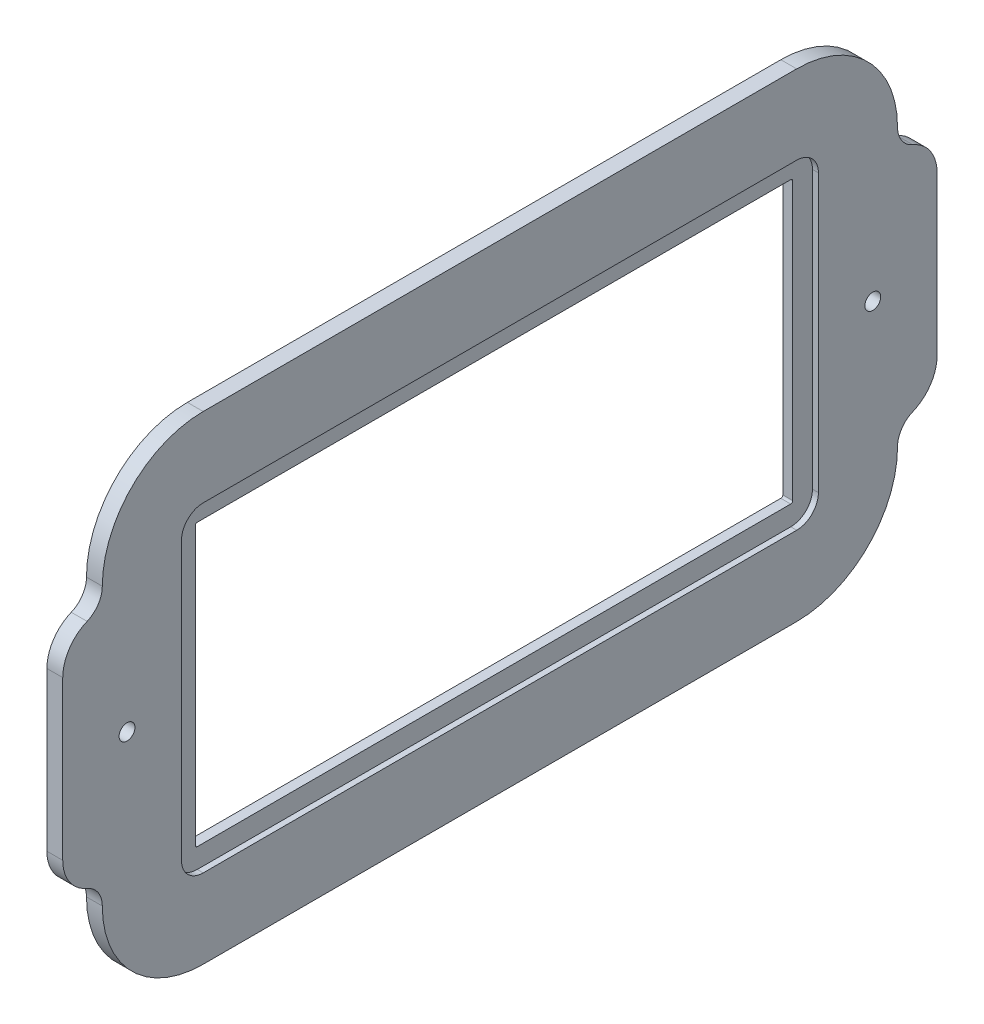
SolidWorks part; units mm, degrees
other "Weld Folder"
material "Ст 3 ГОСТ 380-88"
ref_plane "Front Plane" through (0, 0, 0) normal (0, 0, 1) x (1, 0, 0)
ref_plane "Top Plane" through (0, 0, 0) normal (0, 1, 0) x (1, 0, 0)
ref_plane "Right Plane" through (0, 0, 0) normal (1, 0, 0) x (0, 0, -1)
sketch "Sketch1" plane through (0, 0, 0) normal (0, 0, 1) x (1, 0, 0)
  line L0 (-3, 96) -> (-3, 81) construction
  line L1 (-3, 121) -> (-3, 81)
  line L2 (-3, 81) -> (-6, 81) construction
  line L3 (-3, 81) -> (-6, 81)
  line L4 (-6, 81) -> (-6, 71) construction
  line L5 (-6, 81) -> (-6, 71)
  line L6 (-3, 121) -> (-11, 121)
  line L7 (-11, 121) -> (-11, 71)
  line L8 (-11, 71) -> (-6, 71)
  dimension "D1" = 40
  dimension "D2" = 10
  dimension "D3" = 8
sketch "Sketch2" plane through (0, 0, 0) normal (1, 0, 0) x (0, 0, -1)
  line L4 (150, 92) -> (-150, 92)
  line L5 (-172, 70) -> (-172, -70)
  line L6 (-150, -92) -> (150, -92)
  line L7 (172, -70) -> (172, 70)
  line L8 (150, 92) -> (-150, 92)
  line L9 (-172, 70) -> (-172, -70)
  line L10 (-150, -92) -> (150, -92)
  line L11 (172, -70) -> (172, 70)
  arc A4 (-150, 92) -> (-172, 70) centre (-150, 70) ccw
  arc A5 (-172, -70) -> (-150, -92) centre (-150, -70) ccw
  arc A6 (150, -92) -> (172, -70) centre (150, -70) ccw
  arc A7 (172, 70) -> (150, 92) centre (150, 70) ccw
  arc A8 (-150, 92) -> (-172, 70) centre (-150, 70) ccw
  arc A9 (-172, -70) -> (-150, -92) centre (-150, -70) ccw
  arc A10 (150, -92) -> (172, -70) centre (150, -70) ccw
  arc A11 (172, 70) -> (150, 92) centre (150, 70) ccw
  dimension "D1" = 0
sweep "Sweep1" add profiles "Sketch1" path "Sketch2"
sketch "Sketch5" plane through (-11, 0, 0) normal (-1, 0, 0) x (0, 0, 1)
  line L0 (201, -70) -> (201, 70) construction
  line L1 (0, 121) -> (-150, 121) construction
  line L2 (-201, 70) -> (-201, -70) construction
  line L3 (-150, -121) -> (150, -121) construction
  line L4 (201, -70) -> (201, 70)
  line L5 (150, 121) -> (-150, 121)
  line L6 (-201, 70) -> (-201, -70)
  line L7 (-150, -121) -> (150, -121)
  line L8 (0, 71) -> (-150, 71) construction
  line L9 (-151, 70) -> (-151, -70) construction
  line L10 (150, 71) -> (0, 71) construction
  line L11 (-150, -71) -> (150, -71) construction
  line L12 (151, -70) -> (151, 70) construction
  line L13 (0, 71) -> (-150, 71)
  line L14 (-151, 70) -> (-151, -70)
  line L15 (150, 71) -> (0, 71)
  line L16 (-150, -71) -> (150, -71)
  line L17 (151, -70) -> (151, 70)
  arc A0 (201, 70) -> (150, 121) centre (150, 70) ccw construction
  arc A1 (-150, 121) -> (-201, 70) centre (-150, 70) ccw construction
  arc A2 (-201, -70) -> (-150, -121) centre (-150, -70) ccw construction
  arc A3 (150, -121) -> (201, -70) centre (150, -70) ccw construction
  arc A4 (201, 70) -> (150, 121) centre (150, 70) ccw
  arc A5 (-150, 121) -> (-201, 70) centre (-150, 70) ccw
  arc A6 (-201, -70) -> (-150, -121) centre (-150, -70) ccw
  arc A7 (150, -121) -> (201, -70) centre (150, -70) ccw
  arc A8 (-150, 71) -> (-151, 70) centre (-150, 70) ccw construction
  arc A9 (-151, -70) -> (-150, -71) centre (-150, -70) ccw construction
  arc A10 (151, 70) -> (150, 71) centre (150, 70) ccw construction
  arc A11 (150, -71) -> (151, -70) centre (150, -70) ccw construction
  arc A12 (-150, 71) -> (-151, 70) centre (-150, 70) ccw
  arc A13 (-151, -70) -> (-150, -71) centre (-150, -70) ccw
  arc A14 (151, 70) -> (150, 71) centre (150, 70) ccw
  arc A15 (150, -71) -> (151, -70) centre (150, -70) ccw
extrude "Boss-Extrude1" add sketch "Sketch5" against normal up to surface (8 mm away) up to face at (-3, 0, 181)
sketch "Sketch7" plane through (-3, 0, 0) normal (1, 0, 0) x (0, 0, -1)
  line L25 (161, -70) -> (161, 70)
  line L26 (-150, -81) -> (150, -81)
  line L27 (-161, 70) -> (-161, -70)
  line L28 (150, 81) -> (-150, 81)
  line L29 (161, -70) -> (161, 70)
  line L30 (-150, -81) -> (150, -81)
  line L31 (-161, 70) -> (-161, -70)
  line L32 (150, 81) -> (-150, 81)
  arc A19 (161, 70) -> (150, 81) centre (150, 70) ccw
  arc A20 (150, -81) -> (161, -70) centre (150, -70) ccw
  arc A21 (-161, -70) -> (-150, -81) centre (-150, -70) ccw
  arc A22 (-150, 81) -> (-161, 70) centre (-150, 70) ccw
  arc A23 (161, 70) -> (150, 81) centre (150, 70) ccw
  arc A24 (150, -81) -> (161, -70) centre (150, -70) ccw
  arc A25 (-161, -70) -> (-150, -81) centre (-150, -70) ccw
  arc A26 (-150, 81) -> (-161, 70) centre (-150, 70) ccw
  dimension "D1" = 10
extrude "Cut-Extrude2" cut sketch "Sketch7" against normal blind 3
sketch "Sketch3" plane through (-3, 0, 0) normal (1, 0, 0) x (0, 0, -1)
  line L0 (-188.5, 70) -> (-188.5, -70) construction
  line L6 (-23.8877, 0) -> (36.326, 0) construction
  line L7 (0, 21.9954) -> (0, -24.3228) construction
  line L11 (-176, 70) -> (-201, 70) construction
  circle A1 centre (-188.5, 0) radius 4
  circle A3 centre (188.5, 0) radius 4
extrude "Cut-Extrude1" cut sketch "Sketch3" against normal through all
sketch "Sketch8" plane through (-3, 0, 0) normal (1, 0, 0) x (0, 0, -1)
  line L0 (0, 39.6659) -> (0, -39.6659) construction
  line L1 (-201, -70) -> (-201, 70) construction
  line L2 (-201, -70) -> (-201, 70)
  line L3 (-221, -40) -> (-221, 40)
  line L4 (-221, -70) -> (-221, 70) construction
  line L5 (-22.1812, 0) -> (24.3671, 0) construction
  arc A0 (-221, 40) -> (-208.6923, 58.4615) centre (-201, 40) cw
  arc A1 (-201, 70) -> (-208.6923, 58.4615) centre (-213.5, 70) cw
  arc A2 (-221, -40) -> (-208.6923, -58.4615) centre (-201, -40) ccw
  arc A3 (-201, -70) -> (-208.6923, -58.4615) centre (-213.5, -70) ccw
  dimension "D3" = 20
  dimension "D2" = 80
  dimension "D1" = 20
extrude "Boss-Extrude2" add sketch "Sketch8" against normal up to surface (8 mm away)
mirror "Mirror1" about plane through (0, 0, 0) normal (0, 0, 1) of "Boss-Extrude2"
